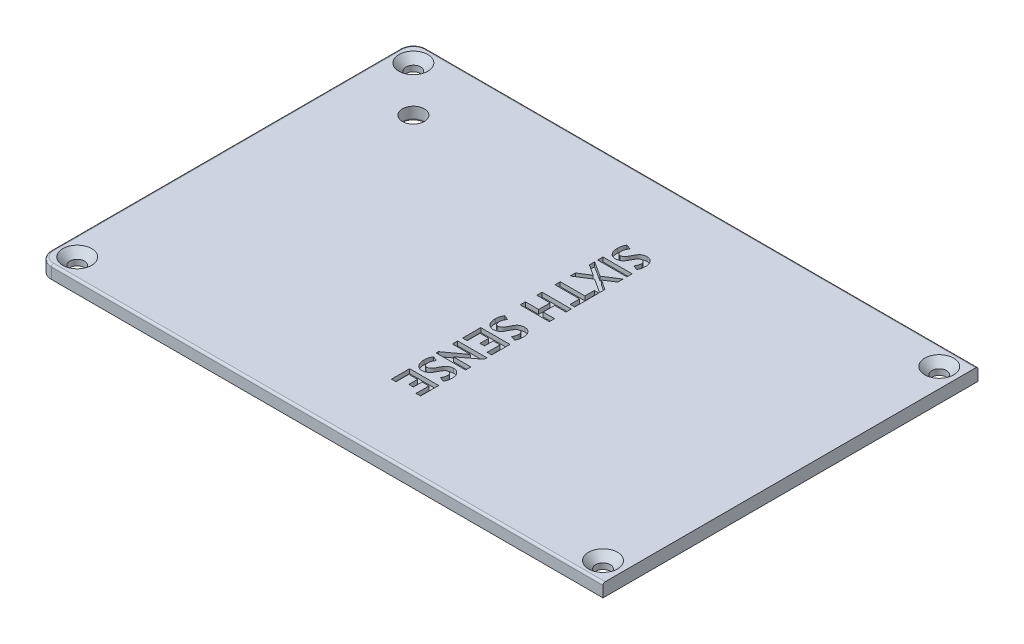
SolidWorks part; units mm, degrees
ref_plane "Front Plane" through (0, 0, 0) normal (0, 0, 1) x (1, 0, 0)
ref_plane "Top Plane" through (0, 0, 0) normal (0, 1, 0) x (1, 0, 0)
ref_plane "Right Plane" through (0, 0, 0) normal (1, 0, 0) x (0, 0, -1)
sketch "Sketch1" plane through (0, 0, 0) normal (0, 1, 0) x (1, 0, 0)
  line L1 (-65.5, -43.5) -> (65.5, -43.5)
  line L2 (-65.5, -43.5) -> (-65.5, 43.5)
  line L3 (-65.5, 43.5) -> (65.5, 43.5)
  line L4 (65.5, -43.5) -> (65.5, 43.5)
  line L5 (-65.5, -43.5) -> (65.5, 43.5) construction
  line L6 (-65.5, 43.5) -> (65.5, -43.5) construction
  point P0 (0, 0)
  dimension "D1" = 131
  dimension "D2" = 87
extrude "Boss-Extrude1" add sketch "Sketch1" along normal mid plane 3
sketch "Sketch2" plane through (0, 1.5, 0) normal (0, 1, 0) x (1, 0, 0)
  line L0 (-65.5, 43.5) -> (-65.5, -43.5) construction
  line L1 (65.5, 43.5) -> (-65.5, 43.5) construction
  line L2 (-65.5, -43.5) -> (65.5, -43.5) construction
  line L3 (65.5, -43.5) -> (65.5, 43.5) construction
  point P0 (-61, 39)
  point P1 (61, 39)
  point P2 (61, -39)
  point P3 (-61, -39)
  dimension "D1" = 4.5
  dimension "D2" = 4.5
  dimension "D3" = 4.5
  dimension "D4" = 4.5
hole_wizard "CSK for M3 SFHCS1" positions "Sketch3" profile "Sketch4" countersink size "M3" standard "ANSI Metric" end condition through all
sketch "Sketch3" plane through (0, 1.5, 0) normal (0, 1, 0) x (1, 0, 0)
  point P0 (-61, 39)
  point P3 (-61, -39)
  point P6 (61, -39)
  point P9 (61, 39)
sketch "Sketch4" plane through (-61, 1.5, -39) normal (1, 0, 0) x (0, 0, 1)
  line L0 (0, 0) -> (0, 3)
  line L1 (0, 3) -> (1.7, 3)
  line L2 (1.7, 3) -> (1.7, 1.66)
  line L3 (1.7, 1.66) -> (3.36, 0)
  line L5 (3.36, 0) -> (0, 0)
  line L6 (-1.7, 1.66) -> (-3.36, 0) construction
  line L11 (0, -6.35) -> (0, 107.95) construction
  dimension "Thru Hole Dia." = 3.4
  dimension "Thru Hole Depth" = 3
  dimension "Near C'Sink Dia." = 6.72
  dimension "Near C'Sink Angle" = 90
sketch "Sketch5" plane through (0, 1.5, 0) normal (0, 1, 0) x (1, 0, 0)
  line L2 (65.5, 43.5) -> (-65.5, 43.5) construction
  line L3 (-65.5, 43.5) -> (-65.5, -43.5) construction
  circle A0 centre (-50.5, 28.5) radius 2.55
  dimension "D1" = 5.1
  dimension "D2" = 15
  dimension "D3" = 15
extrude "Cut-Extrude1" cut sketch "Sketch5" against normal through all
fillet "Fillet3" radius 0.5 1 edges at (-50.5, -1.5, -25.95)
sketch "Sketch6" plane through (0, 1.5, 0) normal (0, 1, 0) x (1, 0, 0)
  line L0 (0, 40.5) -> (0, -40.5) construction
  text T0 "SIXTH SENSE" font "Trebuchet MS" height in points 26
  point P3 (0, 0)
  dimension "D1" = 81
extrude "Cut-Extrude2" cut sketch "Sketch6" against normal blind 1
fillet "Fillet4" radius 3 2 edges at (-65.5, 0, -43.5) (-65.5, 0, 43.5)
fillet "Fillet5" radius 0.5 5 edges at (1.5, 1.5, -43.5) (-64.6213, 1.5, -42.6213) (1.5, 1.5, 43.5) (-64.6213, 1.5, 42.6213) (-65.5, 1.5, 0)
equation "\"D2@Sketch2\"=\"D1@Sketch2\""
equation "\"D3@Sketch2\"=\"D1@Sketch2\""
equation "\"D4@Sketch2\"=\"D1@Sketch2\""
